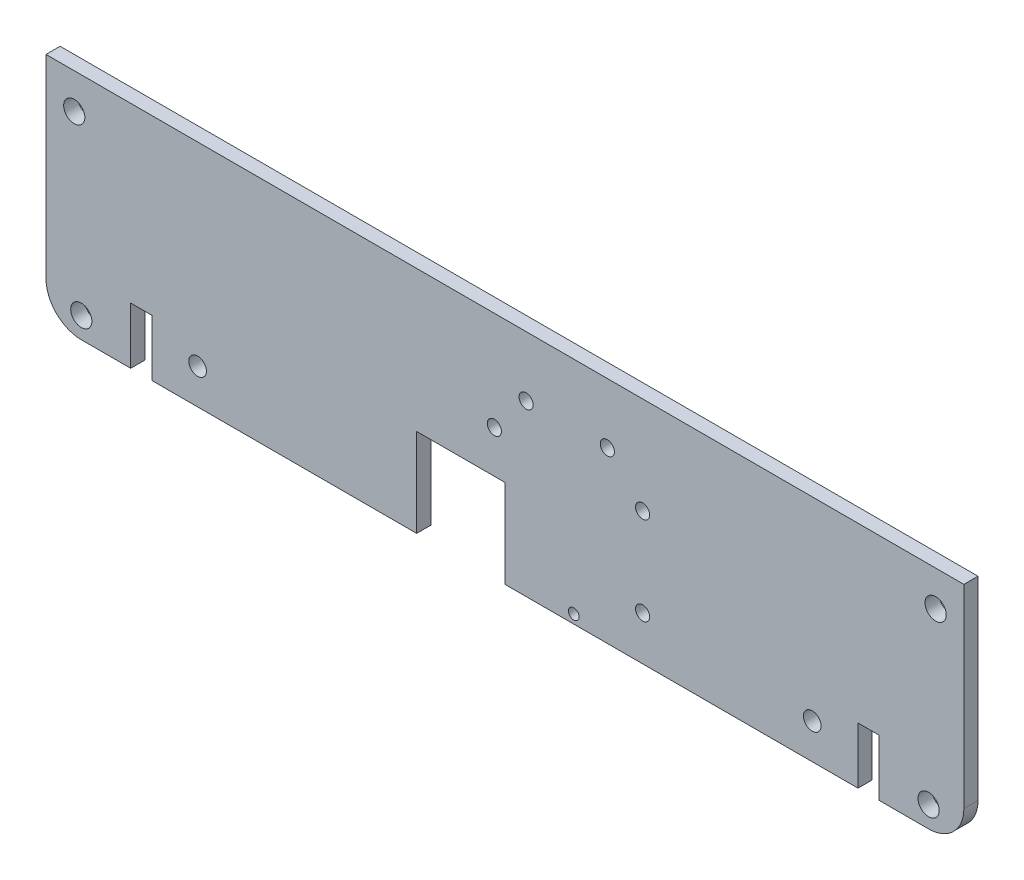
SolidWorks part; units mm, degrees
ref_plane "Front Plane" through (0, 0, 0) normal (0, 0, 1) x (1, 0, 0)
ref_plane "Top Plane" through (0, 0, 0) normal (0, 1, 0) x (1, 0, 0)
ref_plane "Right Plane" through (0, 0, 0) normal (1, 0, 0) x (0, 0, -1)
sketch "Sketch1" plane through (0, 0, 0) normal (0, 0, 1) x (1, 0, 0)
  line L1 (-130, 32.5) -> (130, 32.5)
  line L2 (-130, 32.5) -> (-130, -32.5)
  line L3 (-130, -32.5) -> (130, -32.5)
  line L4 (130, 32.5) -> (130, -32.5)
  line L5 (-130, 32.5) -> (130, -32.5) construction
  line L6 (-130, -32.5) -> (130, 32.5) construction
  point P0 (0, 0)
  dimension "D1" = 65
  dimension "D2" = 260
extrude "Boss-Extrude2" add sketch "Sketch1" along normal blind 4
sketch "Sketch3" plane through (0, 0, 0) normal (0, 0, -1) x (-1, 0, 0)
  circle A1 centre (120, -26.5) radius 3 construction
  circle A2 centre (-120, -26.5) radius 3 construction
  circle A4 centre (120, -26.5) radius 3
  circle A5 centre (-122, 22.5) radius 3 construction
  circle A6 centre (122, 22.5) radius 3 construction
  circle A7 centre (-120, -26.5) radius 3
  circle A8 centre (-122, 22.5) radius 3
  circle A9 centre (122, 22.5) radius 3
extrude "Cut-Extrude2" cut sketch "Sketch3" against normal through all
fillet "Fillet1" radius 10 2 edges at (-130, -32.5, 2) (130, -32.5, 2)
sketch "Sketch4" plane through (0, 0, 0) normal (0, 0, -1) x (-1, 0, 0)
  line L2 (120, -32.5) -> (-120, -32.5) construction
  line L3 (0, -32.5) -> (25, -32.5)
  line L4 (0, -32.5) -> (0, -7.5)
  line L6 (0, -7.5) -> (25, -7.5)
  line L7 (25, -32.5) -> (25, -7.5)
  dimension "D1" = 25
  dimension "D2" = 25
extrude "Cut-Extrude3" cut sketch "Sketch4" against normal blind 10
sketch "Sketch5" plane through (0, 0, 0) normal (0, 0, -1) x (-1, 0, 0)
  line L0 (0, -32.5) -> (-120, -32.5) construction
  line L1 (-106, -32.5) -> (-100, -32.5)
  line L2 (-106, -32.5) -> (-106, -16.5)
  line L3 (-106, -16.5) -> (-100, -16.5)
  line L4 (-100, -32.5) -> (-100, -16.5)
  line L5 (-130, -22.5) -> (-130, 32.5) construction
  line L6 (0, 0) -> (0, 32.5) construction
  line L7 (-130, 32.5) -> (130, 32.5) construction
  line L8 (100, -32.5) -> (100, -16.5)
  line L9 (106, -16.5) -> (100, -16.5)
  line L10 (106, -32.5) -> (106, -16.5)
  line L11 (106, -32.5) -> (100, -32.5)
  dimension "D1" = 24
  dimension "D2" = 6
  dimension "D3" = 16
extrude "Cut-Extrude4" cut sketch "Sketch5" against normal through all
sketch "Sketch6" plane through (0, 0, 0) normal (0, 0, -1) x (-1, 0, 0)
  circle A0 centre (87.05, -22.5) radius 2.5 construction
  circle A1 centre (-87.05, -22.5) radius 2.5 construction
  circle A2 centre (87.05, -22.5) radius 2.5
  circle A3 centre (-87.05, -22.5) radius 2.5
extrude "Cut-Extrude5" cut sketch "Sketch6" against normal through all
sketch "Sketch7" plane through (0, 0, 0) normal (0, 0, -1) x (-1, 0, 0)
  line L0 (0, -7.5) -> (0, -32.5) construction
  line L1 (0, -32.5) -> (-100, -32.5) construction
  circle A0 centre (-39, -20) radius 2
  circle A1 centre (-39, 5) radius 2
  circle A2 centre (-29, 15.5) radius 2
  circle A3 centre (-6, 15.5) radius 2
  circle A4 centre (3, 4.5) radius 2
  circle A5 centre (-19.5, -30) radius 1.5
  dimension "D1" = 4
  dimension "D2" = 39
  dimension "D3" = 12.5
  dimension "D9" = 11
  dimension "D10" = 4
  dimension "D11" = 3
  dimension "D12" = 2.5
  dimension "D13" = 19.5
  dimension "D4" = 25
  dimension "D5" = 48
  dimension "D6" = 10
  dimension "D7" = 23
  dimension "D8" = 3
extrude "Cut-Extrude6" cut sketch "Sketch7" against normal blind 10
